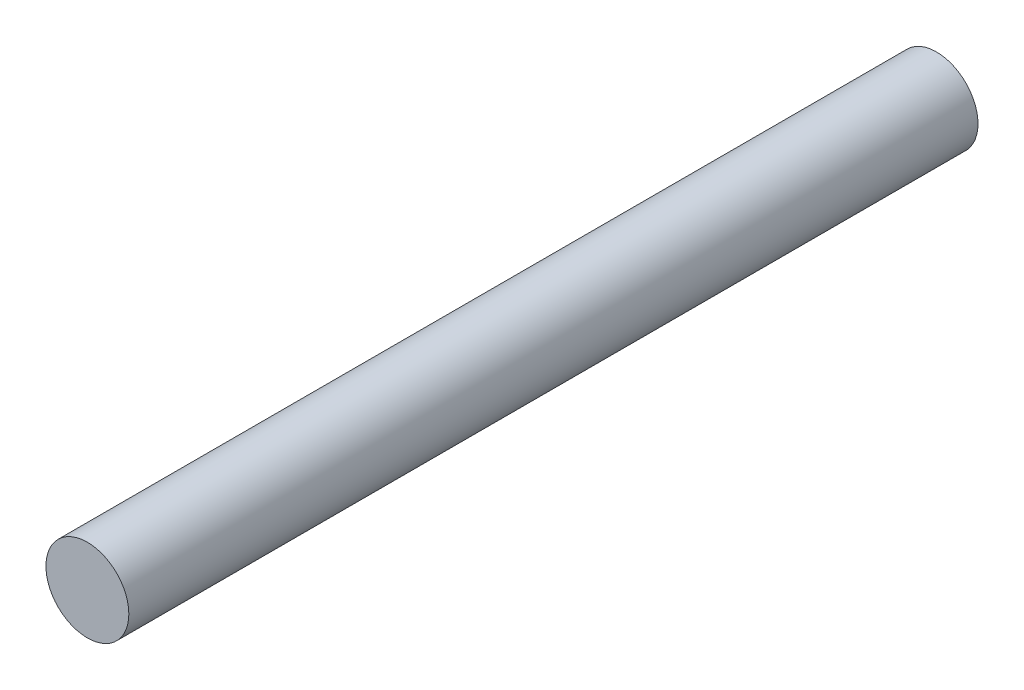
SolidWorks part; units mm, degrees
ref_plane "Front Plane" through (0, 0, 0) normal (0, 0, 1) x (1, 0, 0)
ref_plane "Top Plane" through (0, 0, 0) normal (0, 1, 0) x (1, 0, 0)
ref_plane "Right Plane" through (0, 0, 0) normal (1, 0, 0) x (0, 0, -1)
sketch "Sketch1" plane through (0, 0, 0) normal (0, 0, 1) x (1, 0, 0)
  circle A0 centre (0, 0) radius 4.54
  dimension "D1" = 9.08
extrude "Boss-Extrude1" add sketch "Sketch1" along normal blind 60 and the other way blind 33
